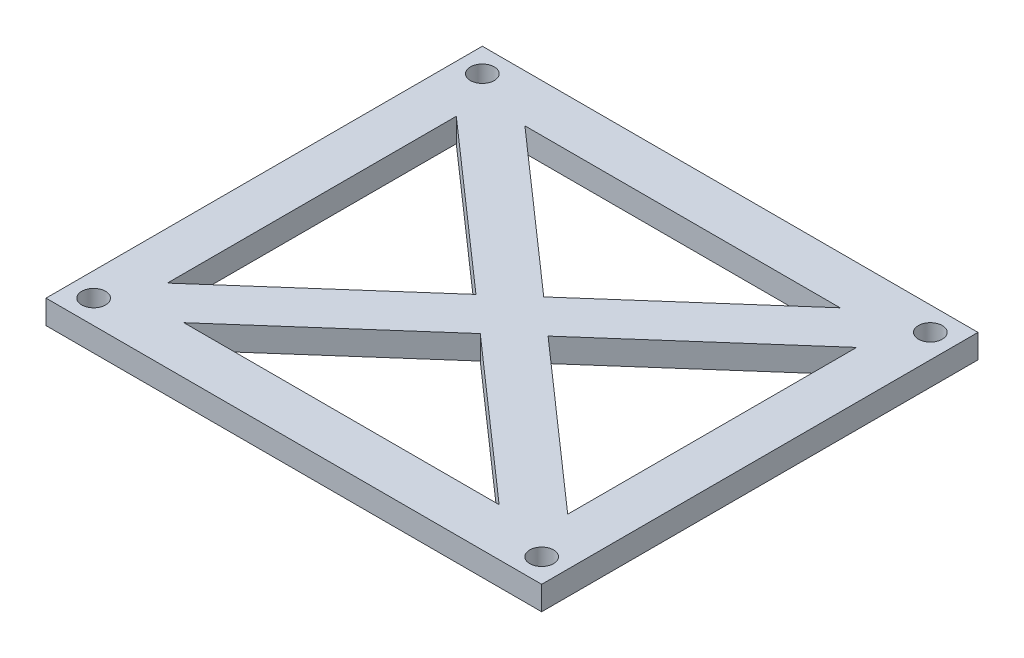
SolidWorks part; units mm, degrees
material "Acrylic (Medium-high impact)"
ref_plane "Front Plane" through (0, 0, 0) normal (0, 0, 1) x (1, 0, 0)
ref_plane "Top Plane" through (0, 0, 0) normal (0, 1, 0) x (1, 0, 0)
ref_plane "Right Plane" through (0, 0, 0) normal (1, 0, 0) x (0, 0, -1)
sketch "Sketch1" plane through (0, 0, 0) normal (0, 1, 0) x (1, 0, 0)
  line L1 (33.02, 24.7422) -> (-33.02, 24.7422)
  line L2 (33.02, 24.7422) -> (33.02, -33.3933)
  line L3 (33.02, -33.3933) -> (-33.02, -33.3933)
  line L4 (-33.02, 24.7422) -> (-33.02, -33.3933)
  line L6 (-26.67, -23.5734) -> (-4.8051, -4.3255)
  line L8 (-21.0015, 18.3922) -> (0, -0.0956)
  line L9 (-26.67, 14.9223) -> (-4.8051, -4.3255)
  line L10 (0, -0.0956) -> (21.0015, 18.3922)
  line L11 (-26.67, 14.9223) -> (-26.67, -23.5734)
  line L14 (0, -8.5555) -> (21.0015, -27.0433)
  line L15 (4.8051, -4.3255) -> (26.67, 14.9223)
  line L19 (4.8051, -4.3255) -> (26.67, -23.5734)
  line L20 (-21.0015, -27.0433) -> (0, -8.5555)
  line L21 (21.0015, -27.0433) -> (-21.0015, -27.0433)
  line L22 (-26.67, 24.7422) -> (-26.67, -33.3933) construction
  line L26 (21.0015, 18.3922) -> (-21.0015, 18.3922)
  line L28 (26.67, 14.9223) -> (26.67, -23.5734)
  circle A0 centre (29.845, 21.5672) radius 1.5875
  circle A1 centre (29.845, -30.2183) radius 1.5875
  circle A2 centre (-29.845, -30.2183) radius 1.5875
  circle A3 centre (-29.845, 21.5672) radius 1.5875
extrude "Boss-Extrude1" add sketch "Sketch1" along normal blind 3.175
